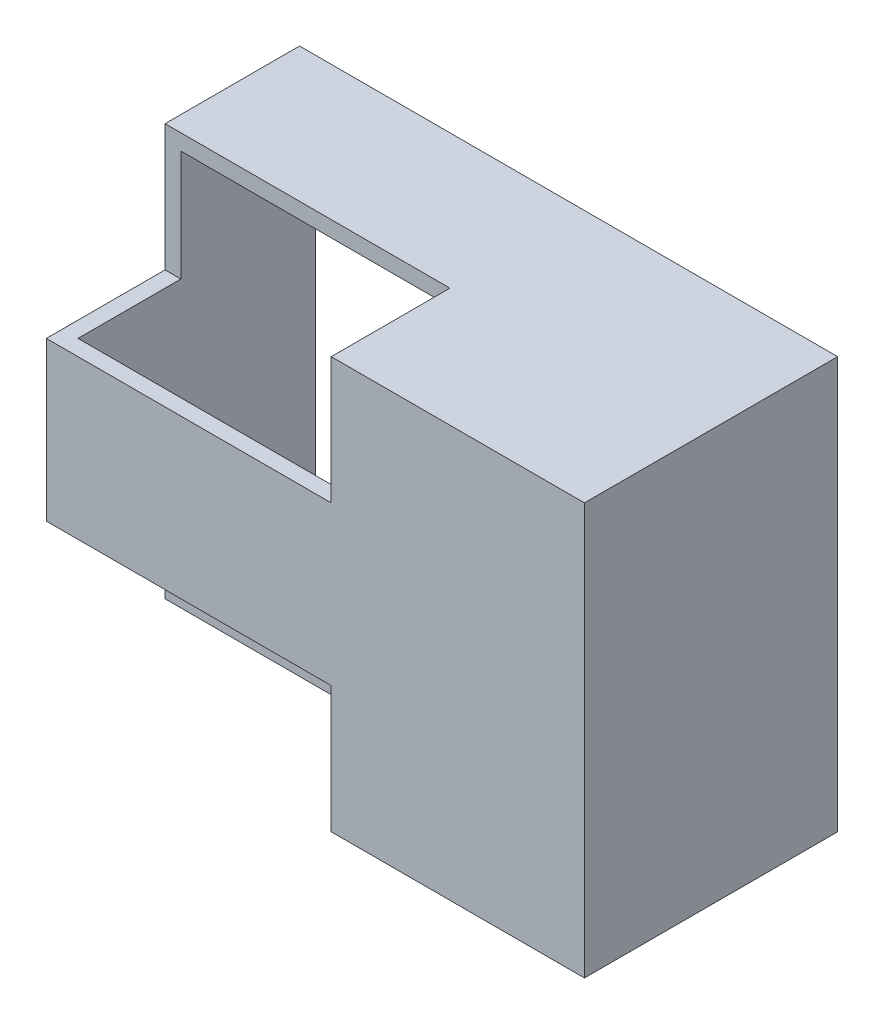
SolidWorks part; units mm, degrees
ref_plane "Front Plane" through (0, 0, 0) normal (0, 0, 1) x (1, 0, 0)
ref_plane "Top Plane" through (0, 0, 0) normal (0, 1, 0) x (1, 0, 0)
ref_plane "Right Plane" through (0, 0, 0) normal (1, 0, 0) x (0, 0, -1)
sketch "Sketch1" plane through (0, 0, 0) normal (0, 0, 1) x (1, 0, 0)
  line L1 (-43.18, 33.02) -> (43.18, 33.02)
  line L2 (-43.18, 33.02) -> (-43.18, -33.02)
  line L3 (-43.18, -33.02) -> (43.18, -33.02)
  line L4 (43.18, 33.02) -> (43.18, -33.02)
  line L5 (-43.18, 33.02) -> (43.18, -33.02) construction
  line L6 (-43.18, -33.02) -> (43.18, 33.02) construction
  point P0 (0, 0)
extrude "Boss-Extrude1" add sketch "Sketch1" along normal blind 40.64
sketch "Sketch2" plane through (0, 0, 0) normal (0, 0, -1) x (-1, 0, 0)
  line L1 (-40.64, 30.48) -> (40.64, 30.48)
  line L2 (-40.64, 30.48) -> (-40.64, -30.48)
  line L3 (-40.64, -30.48) -> (40.64, -30.48)
  line L4 (40.64, 30.48) -> (40.64, -30.48)
  line L5 (-40.64, 30.48) -> (40.64, -30.48) construction
  line L6 (-40.64, -30.48) -> (40.64, 30.48) construction
  point P0 (0, 0)
extrude "Cut-Extrude1" cut sketch "Sketch2" against normal blind 38.1
sketch "Sketch3" plane through (0, 0, 40.64) normal (0, 0, 1) x (1, 0, 0)
  line L1 (-43.18, 33.02) -> (2.54, 33.02)
  line L2 (-43.18, 33.02) -> (-43.18, 12.7)
  line L3 (-43.18, 12.7) -> (2.54, 12.7)
  line L4 (2.54, 33.02) -> (2.54, 12.7)
extrude "Cut-Extrude2" cut sketch "Sketch3" against normal blind 19.05
sketch "Sketch4" plane through (0, 0, 40.64) normal (0, 0, 1) x (1, 0, 0)
  line L1 (-43.18, -33.02) -> (2.54, -33.02)
  line L2 (-43.18, -33.02) -> (-43.18, -12.7)
  line L3 (-43.18, -12.7) -> (2.54, -12.7)
  line L4 (2.54, -33.02) -> (2.54, -12.7)
extrude "Cut-Extrude3" cut sketch "Sketch4" against normal blind 19.05
